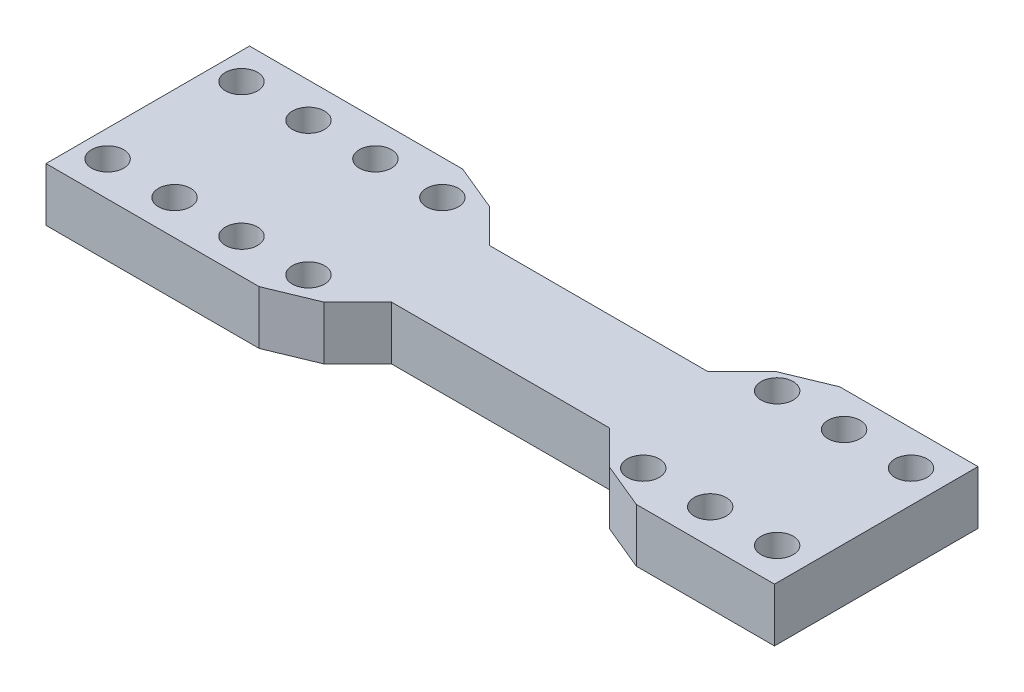
SolidWorks part; units mm, degrees
ref_plane "Front Plane" through (0, 0, 0) normal (0, 0, 1) x (1, 0, 0)
ref_plane "Top Plane" through (0, 0, 0) normal (0, 1, 0) x (1, 0, 0)
ref_plane "Right Plane" through (0, 0, 0) normal (1, 0, 0) x (0, 0, -1)
sketch "Sketch1" plane through (0, 0, 0) normal (0, 1, 0) x (1, 0, 0)
  line L0 (-26.1806, 2.6405) -> (-16.3292, -7.2108)
  line L2 (-70.9695, -35.3595) -> (-70.9695, 2.6405)
  line L4 (65.0305, -35.3595) -> (65.0305, 2.6405)
  line L9 (-65.9695, -3.8595) -> (-40.9695, -3.8595) construction
  line L10 (-65.9695, -3.8595) -> (-65.9695, -28.8595) construction
  line L11 (-65.9695, -28.8595) -> (-40.9695, -28.8595) construction
  line L12 (-40.9695, -3.8595) -> (-40.9695, -28.8595) construction
  line L13 (-16.3292, -7.2108) -> (24.3812, -7.2108)
  line L14 (24.3812, -7.2108) -> (34.2325, 2.6405)
  line L15 (-70.9695, 2.6405) -> (-26.1806, 2.6405)
  line L16 (34.2325, 2.6405) -> (65.0305, 2.6405)
  line L17 (-70.9695, -35.3595) -> (-26.1806, -35.3595)
  line L18 (-26.1806, -35.3595) -> (-16.3292, -25.5081)
  line L19 (-16.3292, -25.5081) -> (24.3812, -25.5081)
  line L20 (24.3812, -25.5081) -> (34.2325, -35.3595)
  line L21 (34.2325, -35.3595) -> (65.0305, -35.3595)
  circle A4 centre (-65.9695, -3.8595) radius 3
  circle A5 centre (-40.9695, -3.8595) radius 3
  circle A6 centre (-40.9695, -28.8595) radius 3
  circle A7 centre (-65.9695, -28.8595) radius 3
  circle A8 centre (-28.4695, -28.8595) radius 3
  circle A9 centre (-53.4695, -3.8595) radius 3
  circle A10 centre (-53.4695, -28.8595) radius 3
  circle A11 centre (-28.4695, -3.8595) radius 3
  circle A12 centre (34.0305, -3.8595) radius 3
  circle A13 centre (59.0305, -28.8595) radius 3
  circle A14 centre (59.0305, -3.8595) radius 3
  circle A15 centre (34.0305, -28.8595) radius 3
  circle A17 centre (46.5305, -28.8595) radius 3
  circle A19 centre (46.5305, -3.8595) radius 3
  point P11 (34.0305, -35.3595)
  dimension "D3" = 6
  dimension "D10" = 125
  dimension "D4" = 25
  dimension "D8" = 6
  dimension "D9" = 5
extrude "Boss-Extrude1" add sketch "Sketch1" along normal blind 10
chamfer "Chamfer1" distance 5 4 edges at (34.2325, 5, 35.3595) (-26.1806, 5, 35.3595) (34.2325, 5, -2.6405) (-26.1806, 5, -2.6405)
